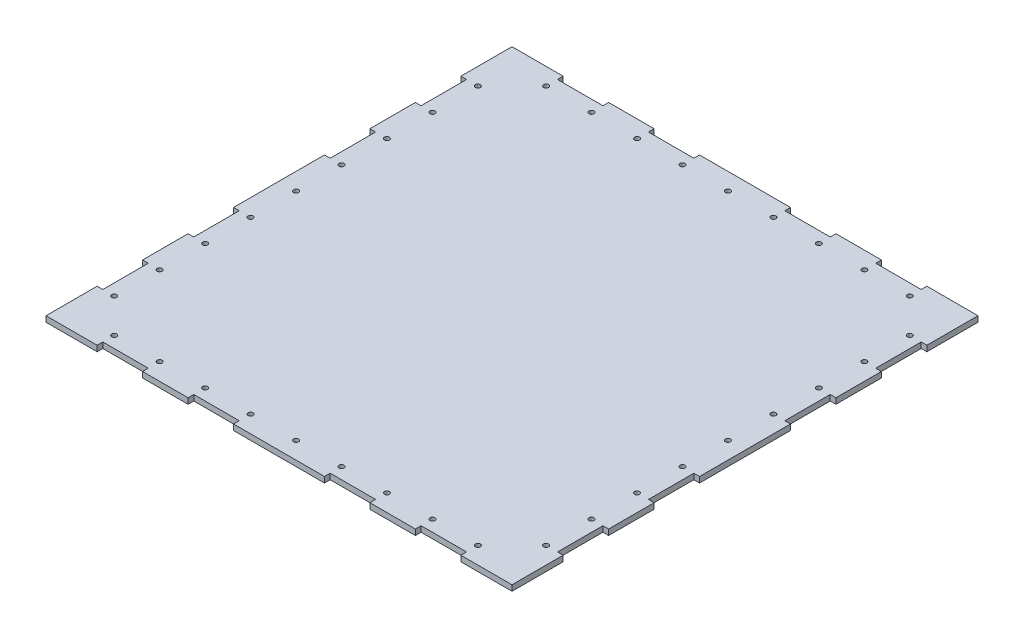
SolidWorks part; units mm, degrees
ref_plane "前视基准面" through (0, 0, 0) normal (0, 0, 1) x (1, 0, 0)
ref_plane "上视基准面" through (0, 0, 0) normal (0, 1, 0) x (1, 0, 0)
ref_plane "右视基准面" through (0, 0, 0) normal (1, 0, 0) x (0, 0, -1)
sketch "草图1" plane through (0, 0, 0) normal (0, 1, 0) x (1, 0, 0)
  line L2 (40, 200) -> (80, 200)
  line L3 (200, 40) -> (200, 80)
  line L5 (200, -40) -> (200, -80)
  line L6 (120, -200) -> (160, -200)
  line L9 (-40, -200) -> (-80, -200)
  line L10 (-200, -40) -> (-200, -80)
  line L13 (-200, 40) -> (-200, 80)
  line L14 (-40, 200) -> (-80, 200)
  line L17 (200, 205) -> (205, 205)
  line L18 (205, 200) -> (205, 205)
  line L21 (205, -200) -> (205, -205)
  line L22 (200, -205) -> (205, -205)
  line L25 (-200, -205) -> (-205, -205)
  line L26 (-205, -200) -> (-205, -205)
  line L29 (-205, 200) -> (-205, 205)
  line L30 (-200, 205) -> (-205, 205)
  line L31 (-200, 205) -> (-160, 205)
  line L32 (-160, 205) -> (-160, 200)
  line L33 (-120, 200) -> (-120, 205)
  line L34 (-120, 205) -> (-80, 205)
  line L35 (-80, 205) -> (-80, 200)
  line L36 (-80, 200) -> (-40, 200)
  line L37 (-40, 200) -> (-40, 205)
  line L38 (-40, 205) -> (40, 205)
  line L39 (40, 205) -> (40, 200)
  line L40 (80, 200) -> (80, 205)
  line L41 (80, 205) -> (120, 205)
  line L42 (120, 205) -> (120, 200)
  line L43 (120, 200) -> (160, 200)
  line L44 (160, 200) -> (160, 205)
  line L45 (160, 205) -> (200, 205)
  line L46 (205, 160) -> (200, 160)
  line L47 (200, 120) -> (205, 120)
  line L48 (205, 120) -> (205, 80)
  line L49 (205, 80) -> (200, 80)
  line L50 (200, 80) -> (200, 40)
  line L51 (200, 40) -> (205, 40)
  line L52 (205, 40) -> (205, -40)
  line L53 (205, -40) -> (200, -40)
  line L54 (200, -80) -> (205, -80)
  line L55 (205, -80) -> (205, -120)
  line L56 (205, -120) -> (200, -120)
  line L57 (200, -120) -> (200, -160)
  line L58 (200, -160) -> (205, -160)
  line L59 (205, 200) -> (205, 160)
  line L60 (205, -160) -> (205, -200)
  line L61 (160, -205) -> (160, -200)
  line L62 (120, -200) -> (120, -205)
  line L63 (120, -205) -> (80, -205)
  line L64 (80, -205) -> (80, -200)
  line L65 (80, -200) -> (40, -200)
  line L66 (40, -200) -> (40, -205)
  line L67 (40, -205) -> (-40, -205)
  line L68 (-40, -205) -> (-40, -200)
  line L69 (-80, -200) -> (-80, -205)
  line L70 (-80, -205) -> (-120, -205)
  line L71 (-120, -205) -> (-120, -200)
  line L72 (-120, -200) -> (-160, -200)
  line L73 (-160, -200) -> (-160, -205)
  line L74 (200, -205) -> (160, -205)
  line L75 (-160, -205) -> (-200, -205)
  line L76 (-205, -160) -> (-200, -160)
  line L77 (-200, -120) -> (-205, -120)
  line L78 (-205, -120) -> (-205, -80)
  line L79 (-205, -80) -> (-200, -80)
  line L80 (-200, -80) -> (-200, -40)
  line L81 (-200, -40) -> (-205, -40)
  line L82 (-205, -40) -> (-205, 40)
  line L83 (-205, 40) -> (-200, 40)
  line L84 (-200, 80) -> (-205, 80)
  line L85 (-205, 80) -> (-205, 120)
  line L86 (-205, 120) -> (-200, 120)
  line L87 (-200, 120) -> (-200, 160)
  line L88 (-200, 160) -> (-205, 160)
  line L89 (-205, -200) -> (-205, -160)
  line L90 (-205, 160) -> (-205, 200)
  line L91 (-120, 200) -> (-160, 200)
  line L92 (-200, 120) -> (-200, 160)
  line L93 (-200, -120) -> (-200, -160)
  line L94 (200, -120) -> (200, -160)
  line L95 (200, 120) -> (200, 160)
  line L96 (120, 200) -> (160, 200)
  circle A0 centre (-190, 0) radius 2.2
  circle A1 centre (-190, 40) radius 2.2
  circle A2 centre (-190, 80) radius 2.2
  circle A3 centre (-190, 120) radius 2.2
  circle A4 centre (-190, 160) radius 2.2
  circle A5 centre (-190, -160) radius 2.2
  circle A6 centre (-190, -120) radius 2.2
  circle A7 centre (-190, -80) radius 2.2
  circle A8 centre (-190, -40) radius 2.2
  circle A9 centre (0, 190) radius 2.2
  circle A10 centre (40, 190) radius 2.2
  circle A11 centre (80, 190) radius 2.2
  circle A12 centre (120, 190) radius 2.2
  circle A13 centre (160, 190) radius 2.2
  circle A14 centre (-160, 190) radius 2.2
  circle A15 centre (-120, 190) radius 2.2
  circle A16 centre (-80, 190) radius 2.2
  circle A17 centre (-40, 190) radius 2.2
  circle A18 centre (190, 0) radius 2.2
  circle A19 centre (190, -40) radius 2.2
  circle A20 centre (190, -80) radius 2.2
  circle A21 centre (190, -120) radius 2.2
  circle A22 centre (190, -160) radius 2.2
  circle A23 centre (190, 160) radius 2.2
  circle A24 centre (190, 120) radius 2.2
  circle A25 centre (190, 80) radius 2.2
  circle A26 centre (190, 40) radius 2.2
  circle A27 centre (0, -190) radius 2.2
  circle A28 centre (-40, -190) radius 2.2
  circle A29 centre (-80, -190) radius 2.2
  circle A30 centre (-120, -190) radius 2.2
  circle A31 centre (-160, -190) radius 2.2
  circle A32 centre (160, -190) radius 2.2
  circle A33 centre (120, -190) radius 2.2
  circle A34 centre (80, -190) radius 2.2
  circle A35 centre (40, -190) radius 2.2
  point P83 (0, 0)
  point P99 (0, 0)
  point P170 (0, 0)
extrude "凸台-拉伸1" add sketch "草图1" along normal blind 5 contours L47 L95 L46 L59 L18 L17 L45 L44 L43 L42 L41 L40 L2 L39 L38 L37 L14 L35 L34 L33 L91 L32 L31 L30 L29 L90 L88 L87 L86 L85 L84 L13 L83 L82 L81 L10 L79 L78 L77 L93 L76 L89 L26 L25 L75 L73 L72 L71 L70 L69 L9
